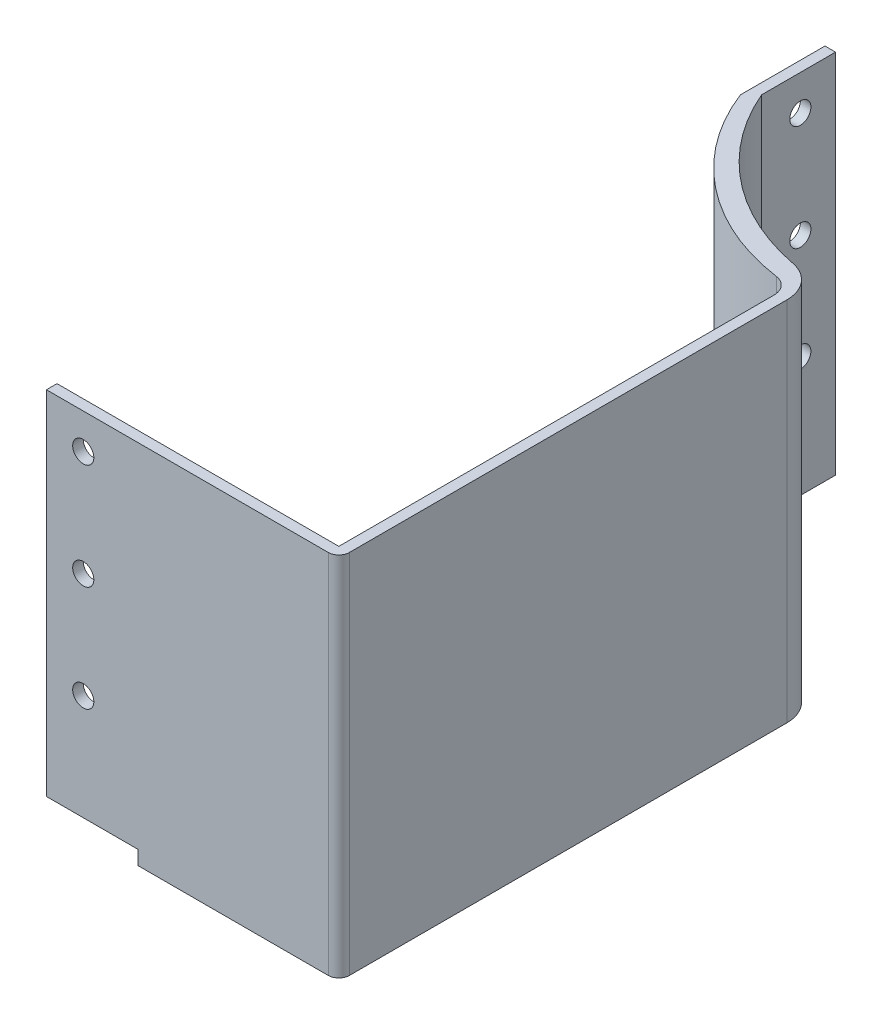
SolidWorks part; units mm, degrees
ref_plane "Спереди" through (0, 0, 0) normal (0, 0, 1) x (1, 0, 0)
ref_plane "Сверху" through (0, 0, 0) normal (0, 1, 0) x (1, 0, 0)
ref_plane "Справа" through (0, 0, 0) normal (1, 0, 0) x (0, 0, -1)
sketch "Эскиз1" plane through (0, 0, 0) normal (0, 1, 0) x (1, 0, 0)
  line L0 (0, 152.2726) -> (0, 176.2726)
  line L1 (0, 176.2726) -> (3, 176.2726)
  line L2 (3, 176.2726) -> (3, 155.2726)
  line L3 (57, 117.2726) -> (57, -18.7274)
  line L4 (57, -18.7274) -> (-26, -18.7274)
  line L5 (-26, -18.7274) -> (-26, -15.7274)
  line L6 (-26, -15.7274) -> (54, -15.7274)
  line L7 (54, -15.7274) -> (54, 112.2726)
  arc A0 (57, 117.2726) -> (3, 155.2726) centre (60.7261, 179.9361) cw
  arc A1 (54, 112.2726) -> (0, 152.2726) centre (58.5616, 174.8808) cw
  dimension "D1" = 3
  dimension "D2" = 3
  dimension "D3" = 128
  dimension "D4" = 80
  dimension "D5" = 3
  dimension "D6" = 24
  dimension "D7" = 54
  dimension "D8" = 64
  dimension "D9" = 136
  dimension "D10" = 21
extrude "Бобышка-Вытянуть1" add sketch "Эскиз1" against normal blind 100
fillet "Скругление1" radius 10 1 edges at (57, -50, -117.2726)
fillet "Скругление2" radius 3 1 edges at (57, -50, 18.7274)
sketch "Эскиз2" plane through (0, 0, 18.7274) normal (0, 0, 1) x (1, 0, 0)
  line L0 (-16, 85.723) -> (-16, -126.8692) construction
  line L2 (-26, -100) -> (-26, 0) construction
  line L3 (-26, 0) -> (54, 0) construction
  circle A0 centre (-15.5536, -10) radius 3
  circle A1 centre (-15.5536, -40) radius 3
  circle A2 centre (-15.5536, -70) radius 3
  point P2 (-78.3054, 85.723)
  point P3 (-15.5536, -126.8692)
  dimension "D2" = 3
  dimension "D4" = 30
  dimension "D1" = 6
  dimension "D3" = 10
  dimension "D5" = 10
extrude "Вырез-Вытянуть1" cut sketch "Эскиз2" against normal blind 60
sketch "Эскиз3" plane through (3, 0, 0) normal (1, 0, 0) x (0, 0, -1)
  line L0 (166.2726, 70.7958) -> (166.2726, -27.9988) construction
  line L1 (176.2726, -100) -> (176.2726, 0) construction
  line L4 (155.2726, 0) -> (176.2726, 0) construction
  circle A0 centre (166.2726, -70) radius 3
  circle A1 centre (166.2726, -40) radius 3
  circle A2 centre (166.2726, -10) radius 3
  dimension "D2" = 10
  dimension "D4" = 30
  dimension "D1" = 10
  dimension "D3" = 3
extrude "Вырез-Вытянуть2" cut sketch "Эскиз3" against normal blind 60
fillet "Скругление3" radius 5 1 edges at (54, -50, -112.2726)
sketch "Эскиз4" plane through (0, -100, 0) normal (0, -1, 0) x (-1, 0, 0)
  line L9 (0, 199.5922) -> (0, -46.5356) construction
  line L10 (-3, 155.2726) -> (-3, 176.2726)
  line L11 (-57, -15.7274) -> (-57, 108.4681)
  line L15 (26, -18.7274) -> (-54, -18.7274) construction
  line L19 (0, -18.7274) -> (-54, -18.7274)
  line L20 (-3, 176.2726) -> (0, 176.2726)
  line L21 (0, 176.2726) -> (0, -18.7274)
  arc A7 (-54, -18.7274) -> (-57, -15.7274) centre (-54, -15.7274) cw
  arc A8 (-57, 108.4681) -> (-48.8861, 118.2886) centre (-47, 108.4681) cw
  arc A9 (-3, 155.2726) -> (-48.8861, 118.2886) centre (-60.7261, 179.9361) cw
  point P0 (0, -18.3249)
extrude "Бобышка-Вытянуть2" add sketch "Эскиз4" along normal blind 4
